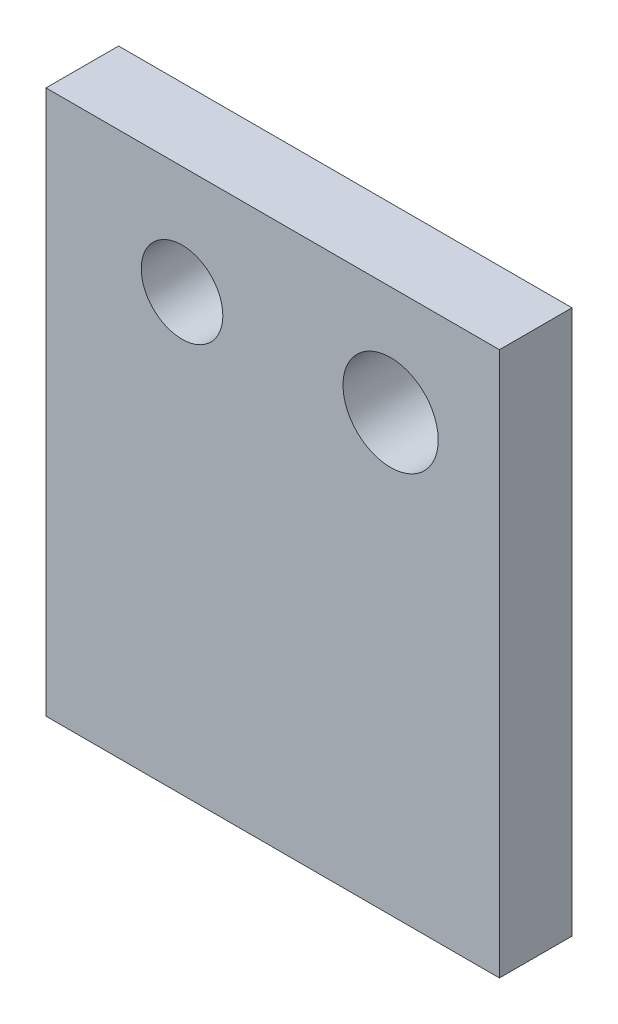
SolidWorks part; units mm, degrees
ref_plane "Front Plane" through (0, 0, 0) normal (0, 0, 1) x (1, 0, 0)
ref_plane "Top Plane" through (0, 0, 0) normal (0, 1, 0) x (1, 0, 0)
ref_plane "Right Plane" through (0, 0, 0) normal (1, 0, 0) x (0, 0, -1)
sketch "Sketch1" plane through (0, 0, 0) normal (0, 0, 1) x (1, 0, 0)
  line L1 (-25, -30) -> (25, -30)
  line L2 (-25, -30) -> (-25, 30)
  line L3 (-25, 30) -> (25, 30)
  line L4 (25, -30) -> (25, 30)
  line L5 (-25, -30) -> (25, 30) construction
  line L6 (-25, 30) -> (25, -30) construction
  circle A0 centre (-10, 18) radius 4.5
  point P0 (0, 0)
  dimension "D3" = 12
  dimension "D5" = 9
  dimension "D1" = 60
  dimension "D2" = 50
  dimension "D4" = 15
extrude "Boss-Extrude1" add sketch "Sketch1" along normal blind 8
sketch "Sketch2" plane through (0, 0, 0) normal (0, 0, 1) x (1, 0, 0)
  line L0 (25, 30) -> (-25, 30) construction
  line L1 (-25, 30) -> (-25, -30) construction
  circle A0 centre (13, 18) radius 5.25
  dimension "D1" = 10.5
  dimension "D2" = 12
  dimension "D3" = 38
extrude "Cut-Extrude2" cut sketch "Sketch2" along normal through all
